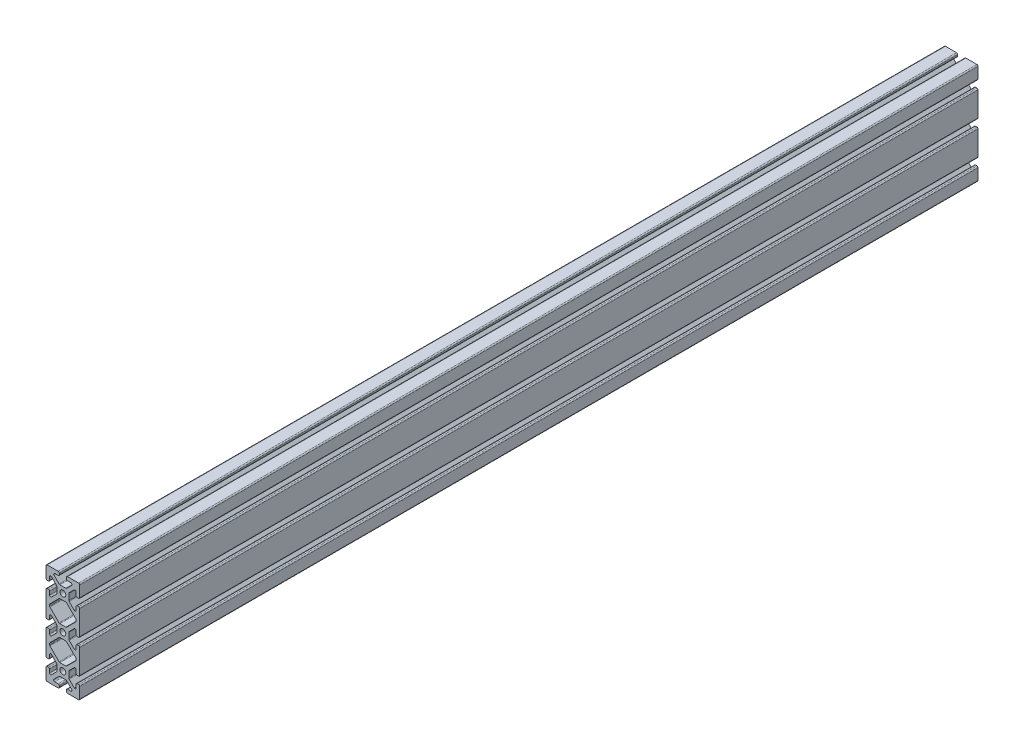
SolidWorks part; units mm, degrees
material "6061 Alloy"
ref_plane "Front Plane" through (0, 0, 0) normal (0, 0, 1) x (1, 0, 0)
ref_plane "Top Plane" through (0, 0, 0) normal (0, 1, 0) x (1, 0, 0)
ref_plane "Right Plane" through (0, 0, 0) normal (1, 0, 0) x (0, 0, -1)
sketch "Sketch1" plane through (0, 0, 0) normal (0, 0, 1) x (1, 0, 0)
  line L0 (0, 0) -> (0, 50000) construction
  line L1 (-19.05, 19.05) -> (19.05, 19.05) construction
  line L2 (-19.05, 19.05) -> (-19.05, -19.05) construction
  line L3 (-19.05, -19.05) -> (19.05, -19.05) construction
  line L4 (19.05, 19.05) -> (19.05, -19.05) construction
  line L5 (-19.05, 19.05) -> (19.05, -19.05) construction
  line L6 (-19.05, -19.05) -> (19.05, 19.05) construction
  line L7 (0, 0) -> (50000, 0) construction
  line L8 (-12.1123, 14.986) -> (-3.8827, 6.7564)
  line L9 (-19.05, 19.05) -> (-4.064, 19.05)
  line L10 (-4.064, 19.05) -> (-4.064, 14.986)
  line L11 (-4.064, 14.986) -> (-12.1123, 14.986)
  line L12 (-3.8827, 6.7564) -> (3.8827, 6.7564)
  line L13 (-6.7564, 3.8827) -> (-6.7564, -3.8827)
  line L14 (-14.986, 12.1123) -> (-6.7564, 3.8827)
  line L15 (-14.986, 4.064) -> (-14.986, 12.1123)
  line L16 (-19.05, 4.064) -> (-14.986, 4.064)
  line L17 (-19.05, 19.05) -> (-19.05, 4.064)
  line L18 (19.05, 4.064) -> (14.986, 4.064)
  line L19 (19.05, 19.05) -> (19.05, 4.064)
  line L20 (14.986, 4.064) -> (14.986, 12.1123)
  line L21 (14.986, 12.1123) -> (6.7564, 3.8827)
  line L22 (6.7564, 3.8827) -> (6.7564, -3.8827)
  line L23 (12.1123, 14.986) -> (3.8827, 6.7564)
  line L24 (4.064, 14.986) -> (12.1123, 14.986)
  line L25 (4.064, 19.05) -> (4.064, 14.986)
  line L26 (19.05, 19.05) -> (4.064, 19.05)
  line L27 (14.986, -12.1123) -> (6.7564, -3.8827)
  line L28 (14.986, -4.064) -> (14.986, -12.1123)
  line L29 (19.05, -4.064) -> (14.986, -4.064)
  line L30 (19.05, -34.036) -> (19.05, -4.064)
  line L31 (-19.05, -34.036) -> (-14.986, -34.036)
  line L32 (-3.8827, -6.7564) -> (-14.986, -17.8597)
  line L33 (-14.986, -34.036) -> (-14.986, -25.9877)
  line L34 (3.8827, -6.7564) -> (14.986, -17.8597)
  line L35 (-3.8827, -6.7564) -> (3.8827, -6.7564)
  line L36 (-14.986, -25.9877) -> (-6.7564, -34.2173)
  line L37 (-3.8827, -31.3436) -> (3.8827, -31.3436)
  line L38 (3.8827, -31.3436) -> (14.986, -20.2403)
  line L39 (-3.8827, -31.3436) -> (-14.986, -20.2403)
  line L40 (-14.986, -12.1123) -> (-6.7564, -3.8827)
  line L41 (-14.986, -4.064) -> (-14.986, -12.1123)
  line L42 (-19.05, -4.064) -> (-14.986, -4.064)
  line L43 (-19.05, -34.036) -> (-19.05, -4.064)
  line L44 (19.05, -34.036) -> (14.986, -34.036)
  line L45 (14.986, -34.036) -> (14.986, -25.9877)
  line L46 (14.986, -25.9877) -> (6.7564, -34.2173)
  line L47 (14.986, -58.3403) -> (14.986, -55.9597)
  line L48 (-14.986, -58.3403) -> (-14.986, -55.9597)
  line L49 (14.986, -50.2123) -> (6.7564, -41.9827)
  line L50 (14.986, -42.164) -> (14.986, -50.2123)
  line L51 (6.7564, -41.9827) -> (6.7564, -34.2173)
  line L52 (19.05, -42.164) -> (14.986, -42.164)
  line L53 (-19.05, -42.164) -> (-19.05, -72.136)
  line L54 (-19.05, -72.136) -> (-14.986, -72.136)
  line L55 (-14.986, -72.136) -> (-14.986, -64.0877)
  line L56 (-14.986, -64.0877) -> (-6.7564, -72.3173)
  line L57 (-3.8827, -44.8564) -> (-14.986, -55.9597)
  line L58 (3.8827, -44.8564) -> (14.986, -55.9597)
  line L59 (-3.8827, -44.8564) -> (3.8827, -44.8564)
  line L60 (-6.7564, -41.9827) -> (-6.7564, -34.2173)
  line L61 (-14.986, -50.2123) -> (-6.7564, -41.9827)
  line L62 (-3.8827, -69.4436) -> (3.8827, -69.4436)
  line L63 (3.8827, -69.4436) -> (14.986, -58.3403)
  line L64 (-14.986, -42.164) -> (-14.986, -50.2123)
  line L65 (-3.8827, -69.4436) -> (-14.986, -58.3403)
  line L66 (-14.986, -17.8597) -> (-14.986, -20.2403)
  line L67 (14.986, -17.8597) -> (14.986, -20.2403)
  line L68 (0, -38.1) -> (-50000, -38.1) construction
  line L69 (-19.05, -42.164) -> (-14.986, -42.164)
  line L70 (19.05, -42.164) -> (19.05, -72.136)
  line L71 (19.05, -72.136) -> (14.986, -72.136)
  line L72 (14.986, -72.136) -> (14.986, -64.0877)
  line L73 (14.986, -64.0877) -> (6.7564, -72.3173)
  line L74 (19.05, -95.25) -> (4.064, -95.25)
  line L75 (4.064, -95.25) -> (4.064, -91.186)
  line L76 (4.064, -91.186) -> (12.1123, -91.186)
  line L77 (12.1123, -91.186) -> (3.8827, -82.9564)
  line L78 (6.7564, -80.0827) -> (6.7564, -72.3173)
  line L79 (14.986, -88.3123) -> (6.7564, -80.0827)
  line L80 (14.986, -80.264) -> (14.986, -88.3123)
  line L81 (19.05, -95.25) -> (19.05, -80.264)
  line L82 (19.05, -80.264) -> (14.986, -80.264)
  line L83 (-19.05, -95.25) -> (-19.05, -80.264)
  line L84 (-19.05, -80.264) -> (-14.986, -80.264)
  line L85 (-14.986, -80.264) -> (-14.986, -88.3123)
  line L86 (-14.986, -88.3123) -> (-6.7564, -80.0827)
  line L87 (-6.7564, -80.0827) -> (-6.7564, -72.3173)
  line L88 (-3.8827, -82.9564) -> (3.8827, -82.9564)
  line L89 (-4.064, -91.186) -> (-12.1123, -91.186)
  line L90 (-4.064, -95.25) -> (-4.064, -91.186)
  line L91 (-19.05, -95.25) -> (-4.064, -95.25)
  line L92 (-12.1123, -91.186) -> (-3.8827, -82.9564)
  circle A0 centre (0, 0) radius 3.3274
  circle A1 centre (0, -38.1) radius 3.3274
  circle A2 centre (0, -76.2) radius 3.3274
  point P0 (0, 0)
  point P28 (0, 6.7564)
  point P32 (6.7564, 0)
  point P44 (-6.7564, 0)
  point P64 (-6.7564, -38.1)
  point P65 (6.7564, -38.1)
  point P74 (-6.7564, -38.1)
  point P75 (6.7564, -38.1)
  point P107 (-6.7564, -76.2)
  point P108 (6.7564, -76.2)
  point P109 (0, -82.9564)
  dimension "D3" = 14.986
  dimension "D2" = 6.6548
  dimension "D1" = 38.1
  dimension "D4" = 4.064
  dimension "D5" = 2.032
  dimension "D6" = 12.2936
extrude "Boss-Extrude1" add sketch "Sketch1" along normal blind 1016
fillet "Fillet1" radius 1.27 84 edges at (-14.986, -34.036, 508) (-19.05, -34.036, 508) (-6.7564, -34.2173, 508) (6.7564, -34.2173, 508) (14.986, -25.9877, 508) (14.986, -34.036, 508) (19.05, -34.036, 508) (-19.05, 4.064, 508) (-14.986, 4.064, 508) (-14.986, 12.1123, 508) (-6.7564, 3.8827, 508) (-6.7564, -3.8827, 508) (-19.05, -4.064, 508) (-14.986, -4.064, 508) (-14.986, -12.1123, 508) (3.8827, -31.3436, 508) (-3.8827, -31.3436, 508) (-3.8827, -6.7564, 508) (3.8827, -6.7564, 508) (14.986, -12.1123, 508) (19.05, -4.064, 508) (14.986, -4.064, 508) (6.7564, -3.8827, 508) (6.7564, 3.8827, 508) (14.986, 4.064, 508) (19.05, 4.064, 508) (14.986, 12.1123, 508) (19.05, 19.05, 508) (4.064, 19.05, 508) (4.064, 14.986, 508) (12.1123, 14.986, 508) (3.8827, 6.7564, 508) (-3.8827, 6.7564, 508) (-12.1123, 14.986, 508) (-4.064, 14.986, 508) (-4.064, 19.05, 508) (-19.05, 19.05, 508) (14.986, -20.2403, 508) (14.986, -17.8597, 508) (-14.986, -20.2403, 508) (-14.986, -17.8597, 508) (-14.986, -88.3123, 508) (-19.05, -95.25, 508) (-4.064, -95.25, 508) (-4.064, -91.186, 508) (-12.1123, -91.186, 508) (-3.8827, -82.9564, 508) (3.8827, -82.9564, 508) (12.1123, -91.186, 508) (4.064, -91.186, 508) (4.064, -95.25, 508) (19.05, -95.25, 508) (19.05, -80.264, 508) (14.986, -80.264, 508) (14.986, -88.3123, 508) (-19.05, -72.136, 508) (-14.986, -72.136, 508) (14.986, -72.136, 508) (19.05, -72.136, 508) (-19.05, -80.264, 508) (-14.986, -80.264, 508) (-6.7564, -80.0827, 508) (6.7564, -80.0827, 508) (-6.7564, -72.3173, 508) (6.7564, -72.3173, 508) (3.8827, -69.4436, 508) (-3.8827, -69.4436, 508) (3.8827, -44.8564, 508) (-3.8827, -44.8564, 508) (-14.986, -64.0877, 508) (14.986, -64.0877, 508) (14.986, -58.3403, 508) (14.986, -55.9597, 508) (-14.986, -58.3403, 508) (-14.986, -55.9597, 508) (-19.05, -42.164, 508) (-14.986, -42.164, 508) (14.986, -50.2123, 508) (-14.986, -50.2123, 508) (19.05, -42.164, 508) (14.986, -42.164, 508) (6.7564, -41.9827, 508) (-6.7564, -41.9827, 508) (-14.986, -25.9877, 508)
